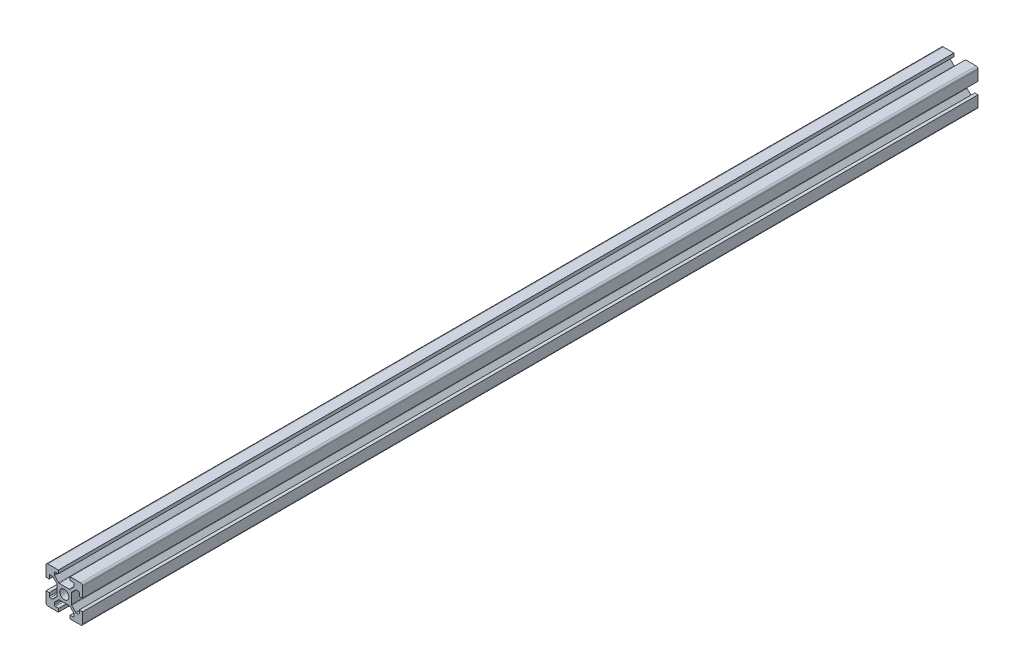
SolidWorks part; units mm, degrees
material "1060 Alloy"
ref_plane "Front Plane" through (0, 0, 0) normal (0, 0, 1) x (1, 0, 0)
ref_plane "Top Plane" through (0, 0, 0) normal (0, 1, 0) x (1, 0, 0)
ref_plane "Right Plane" through (0, 0, 0) normal (1, 0, 0) x (0, 0, -1)
sketch "Sketch1" plane through (0, 0, 0) normal (0, 0, 1) x (1, 0, 0)
  line L0 (20, 0) -> (-8.059, 28.059) construction
  line L1 (0, 0) -> (6.8, 0)
  line L2 (0, 0) -> (0, 6.8)
  line L3 (0, 20) -> (6.8, 20)
  line L4 (20, 0) -> (20, 6.8)
  line L5 (6.8, 20) -> (6.8, 18.2)
  line L6 (20, 20) -> (8.2322, 8.2322) construction
  line L7 (12.95, 6.1) -> (7.05, 6.1)
  line L8 (13.9, 7.05) -> (13.9, 12.95)
  line L9 (12.95, 13.9) -> (7.05, 13.9)
  line L10 (6.1, 7.05) -> (6.1, 12.95)
  line L11 (13.9, 6.1) -> (6.1, 13.9) construction
  line L12 (13.9, 13.9) -> (6.1, 6.1) construction
  line L13 (4.55, 16.4) -> (7.05, 13.9)
  line L14 (13.2, 18.2) -> (13.2, 20)
  line L15 (1.8, 6.8) -> (0, 6.8)
  line L16 (0, 13.2) -> (0, 20)
  line L17 (0, 13.2) -> (1.8, 13.2)
  line L18 (10, 10) -> (10, 13.9) construction
  line L19 (16.4, 4.55) -> (13.9, 7.05)
  line L20 (4.55, 16.4) -> (4.55, 18.2)
  line L21 (4.55, 18.2) -> (6.8, 18.2)
  line L22 (13.2, 18.2) -> (15.45, 18.2)
  line L23 (15.45, 18.2) -> (15.45, 16.4)
  line L24 (15.45, 16.4) -> (12.95, 13.9)
  line L25 (16.4, 4.55) -> (18.2, 4.55)
  line L26 (18.2, 4.55) -> (18.2, 6.8)
  line L27 (20, 6.8) -> (18.2, 6.8)
  line L28 (18.2, 13.2) -> (20, 13.2)
  line L29 (18.2, 13.2) -> (18.2, 15.45)
  line L30 (18.2, 15.45) -> (16.4, 15.45)
  line L31 (16.4, 15.45) -> (13.9, 12.95)
  line L32 (1.8, 4.55) -> (3.6, 4.55)
  line L33 (3.6, 15.45) -> (6.1, 12.95)
  line L34 (3.6, 15.45) -> (1.8, 15.45)
  line L35 (1.8, 15.45) -> (1.8, 13.2)
  line L36 (0, 13.2) -> (1.8, 13.2)
  line L37 (1.8, 6.8) -> (0, 6.8)
  line L38 (3.6, 4.55) -> (6.1, 7.05)
  line L39 (1.8, 6.8) -> (1.8, 4.55)
  line L40 (15.45, 3.6) -> (12.95, 6.1)
  line L41 (4.55, 3.6) -> (7.05, 6.1)
  line L42 (4.55, 1.8) -> (4.55, 3.6)
  line L43 (6.8, 1.8) -> (4.55, 1.8)
  line L44 (6.8, 1.8) -> (6.8, 0)
  line L45 (15.45, 3.6) -> (15.45, 1.8)
  line L46 (15.45, 1.8) -> (13.2, 1.8)
  line L47 (13.2, 0) -> (13.2, 1.8)
  line L48 (13.2, 20) -> (20, 20)
  line L49 (20, 13.2) -> (20, 20)
  line L50 (13.2, 0) -> (20, 0)
  line L51 (6.1, 6.1) -> (-5.5045, -5.5045) construction
  circle A0 centre (10, 10) radius 2.5
  point P25 (10, 16.4)
  point P39 (13.2, 19.1)
  point P46 (0.9, 6.8)
  dimension "D3" = 5
  dimension "D2" = 20
  dimension "D4" = 7.8
  dimension "D5" = 7.8
  dimension "D6" = 6.8
  dimension "D7" = 6.8
  dimension "D8" = 1.8
  dimension "D9" = 10.9
  dimension "D10" = 1.8
  dimension "D11" = 10.9
  dimension "D12" = 20
extrude "Boss-Extrude1" add sketch "Sketch1" along normal blind 490 contours L47 L50 L4 L27 L26 L25 L19 L8 L31 L30 L29 L28 L49 L48 L14 L22 L23 L24 L9 L13 L20 L21 L5 L3 L16 L17 L35 L34 L33 L10 L38 L32 L39 L15 L2 L1 L44 L43 L42 L41 L7 L40 L45 L46 A0
fillet "Fillet1" radius 1 4 edges at (20, 20, 245) (20, 0, 245) (0, 0, 245) (0, 20, 245)
fillet "Fillet2" radius 0.5 6 edges at (4.55, 18.2, 245) (4.55, 16.4, 245) (7.05, 13.9, 245) (15.45, 18.2, 245) (15.45, 16.4, 245) (12.95, 13.9, 245)
fillet "Fillet3" radius 0.5 6 edges at (18.2, 15.45, 245) (16.4, 15.45, 245) (13.9, 12.95, 245) (18.2, 4.55, 245) (13.9, 7.05, 245) (16.4, 4.55, 245)
fillet "Fillet4" radius 0.5 6 edges at (1.8, 15.45, 245) (3.6, 15.45, 245) (6.1, 12.95, 245) (3.6, 4.55, 245) (1.8, 4.55, 245) (6.1, 7.05, 245)
fillet "Fillet5" radius 0.5 6 edges at (7.05, 6.1, 245) (4.55, 3.6, 245) (4.55, 1.8, 245) (15.45, 1.8, 245) (15.45, 3.6, 245) (12.95, 6.1, 245)
